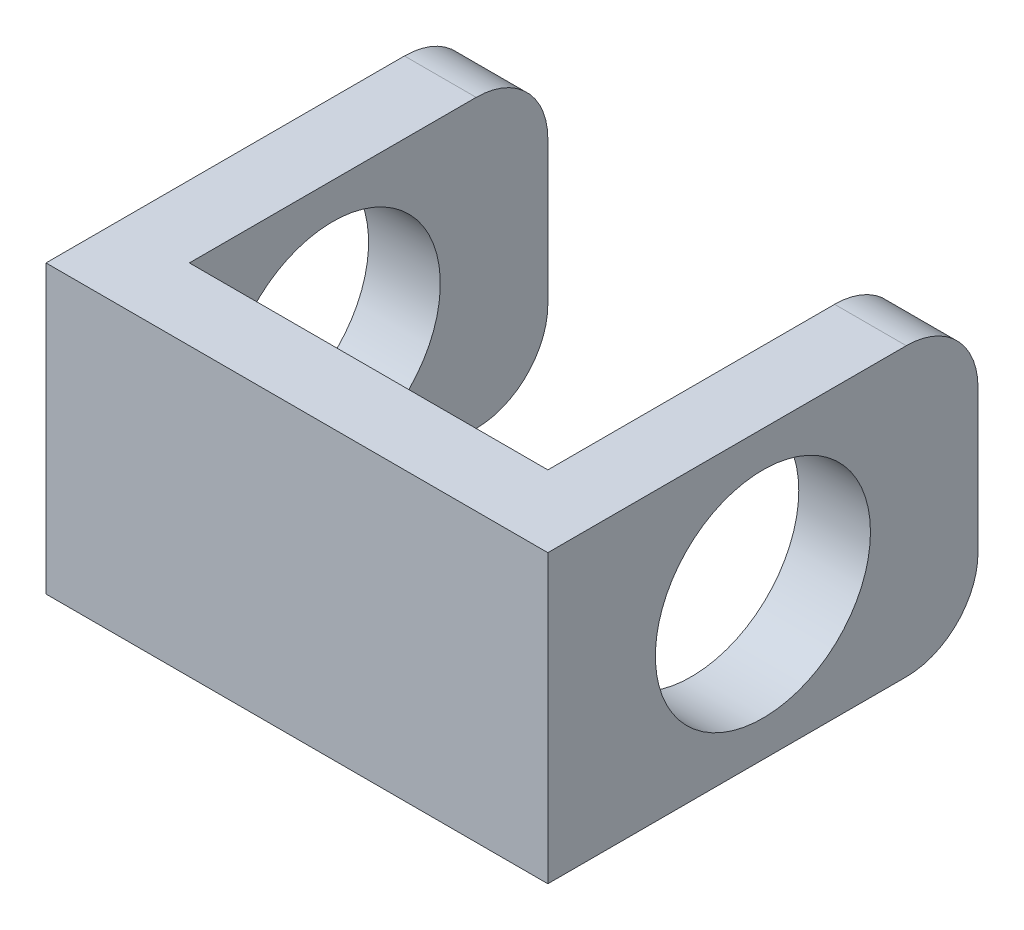
SolidWorks part; units mm, degrees
ref_plane "Front Plane" through (0, 0, 0) normal (0, 0, 1) x (1, 0, 0)
ref_plane "Top Plane" through (0, 0, 0) normal (0, 1, 0) x (1, 0, 0)
ref_plane "Right Plane" through (0, 0, 0) normal (1, 0, 0) x (0, 0, -1)
sketch "Sketch1" plane through (0, 0, 0) normal (0, 0, 1) x (1, 0, 0)
  line L1 (0, 0) -> (50, 0)
  line L2 (0, 0) -> (0, 40)
  line L3 (0, 40) -> (50, 40)
  line L4 (50, 0) -> (50, 40)
  dimension "D1" = 40
  dimension "D2" = 50
extrude "Boss-Extrude1" add sketch "Sketch1" along normal blind 10
sketch "Sketch2" plane through (0, 0, 0) normal (1, 0, 0) x (0, 0, -1)
  line L1 (0, 0) -> (40, 0)
  line L2 (0, 0) -> (0, 40)
  line L3 (0, 40) -> (40, 40)
  line L4 (50, 10) -> (50, 30)
  arc A0 (40, 40) -> (50, 30) centre (40, 30) cw
  arc A1 (50, 10) -> (40, 0) centre (40, 10) cw
  point P7 (50, 40)
  point P10 (50, 0)
  dimension "D3" = 10
  dimension "D1" = 40
  dimension "D2" = 50
extrude "Boss-Extrude2" add sketch "Sketch2" against normal blind 10 separate body
sketch "Sketch3" plane through (50, 0, 0) normal (1, 0, 0) x (0, 0, -1)
  line L1 (-10, 40) -> (40, 40)
  line L2 (-10, 40) -> (-10, 0)
  line L3 (-10, 0) -> (40, 0)
  line L4 (50, 30) -> (50, 10)
  arc A0 (40, 0) -> (50, 10) centre (40, 10) ccw
  arc A1 (50, 30) -> (40, 40) centre (40, 30) ccw
  dimension "D1" = 10
extrude "Boss-Extrude3" add sketch "Sketch3" along normal blind 10
sketch "Sketch4" plane through (0, 0, 10) normal (0, 0, 1) x (1, 0, 0)
  line L1 (60, 40) -> (-10, 40)
  line L2 (60, 40) -> (60, 0)
  line L3 (60, 0) -> (-10, 0)
  line L4 (-10, 40) -> (-10, 0)
extrude "Boss-Extrude4" add sketch "Sketch4" against normal blind 10
sketch "Sketch5" plane through (60, 0, 0) normal (1, 0, 0) x (0, 0, -1)
  line L0 (40, 40) -> (40, 0)
  line L1 (40, 0) -> (50, 20)
  line L2 (50, 10) -> (50, 30) construction
  line L3 (50, 20) -> (35, 20)
  line L4 (50, 20) -> (-10, 20)
  line L5 (-10, 0) -> (-10, 40) construction
  line L6 (20, 20) -> (20, 40)
  line L7 (40, 40) -> (-10, 40) construction
  line L8 (20, 40) -> (20, 0)
  line L9 (40, 0) -> (-10, 0) construction
  circle A1 centre (20, 20) radius 15
  dimension "D1" = 30
extrude "Cut-Extrude1" cut sketch "Sketch5" against normal blind 140 contours L6 A1 L4 | L4 A1 L8 | L8 A1 L4 | L4 A1 L6
